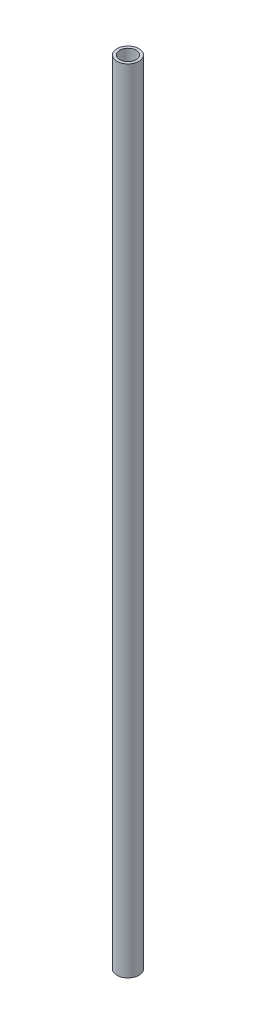
SolidWorks part; units mm, degrees
material "PE Low/Medium Density"
ref_plane "Front Plane" through (0, 0, 0) normal (0, 0, 1) x (1, 0, 0)
ref_plane "Top Plane" through (0, 0, 0) normal (0, 1, 0) x (1, 0, 0)
ref_plane "Right Plane" through (0, 0, 0) normal (1, 0, 0) x (0, 0, -1)
sketch "Sketch1" plane through (0, 0, 0) normal (0, 1, 0) x (1, 0, 0)
  circle A0 centre (0, 0) radius 6.35
  circle A1 centre (0, 0) radius 4.7625
  dimension "D1" = 1.5875
  dimension "D2" = 12.7
extrude "Boss-Extrude1" add sketch "Sketch1" along normal blind 457.2
